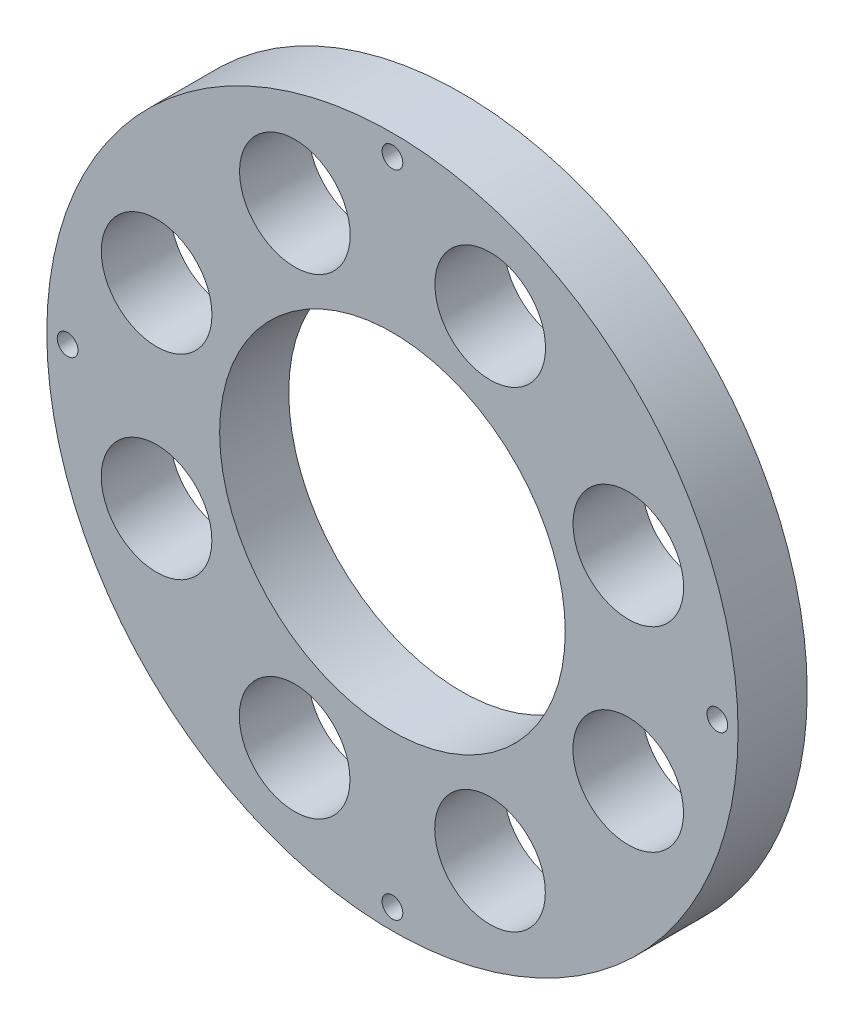
SolidWorks part; units mm, degrees
ref_plane "Front Plane" through (0, 0, 0) normal (0, 0, 1) x (1, 0, 0)
ref_plane "Top Plane" through (0, 0, 0) normal (0, 1, 0) x (1, 0, 0)
ref_plane "Right Plane" through (0, 0, 0) normal (1, 0, 0) x (0, 0, -1)
sketch "Sketch1" plane through (0, 0, 0) normal (0, 0, 1) x (1, 0, 0)
  circle A0 centre (0, 0) radius 50
  circle A1 centre (0, 0) radius 25
extrude "Boss-Extrude1" add sketch "Sketch1" along normal blind 10
sketch "Sketch3" plane through (0, 0, 0) normal (0, 0, -1) x (-1, 0, 0)
  circle A0 centre (-14.1464, 34.1095) radius 8
  circle A1 centre (14.1161, 34.122) radius 8
  circle A2 centre (34.1095, 14.1464) radius 8
  circle A3 centre (34.122, -14.1161) radius 8
  circle A4 centre (14.1464, -34.1095) radius 8
  circle A5 centre (-14.1161, -34.122) radius 8
  circle A6 centre (-34.1095, -14.1464) radius 8
  circle A7 centre (-34.122, 14.1161) radius 8
  point P19 (0, 0)
  dimension "D1" = 8
extrude "Cut-Extrude1" cut sketch "Sketch3" against normal blind 20 contours A0 | A1 | A2 | A3 | A4 | A5 | A6 | A7
sketch "Sketch4" plane through (0, 0, 0) normal (0, 0, -1) x (-1, 0, 0)
  circle A1 centre (0, 46.99) radius 1.5
  circle A2 centre (46.99, 0) radius 1.5
  circle A3 centre (0, -46.99) radius 1.5
  circle A4 centre (-46.99, 0) radius 1.5
  point P0 (0, 0)
  point P14 (0, 0)
  dimension "D1" = 4
extrude "Cut-Extrude2" cut sketch "Sketch4" against normal blind 30
